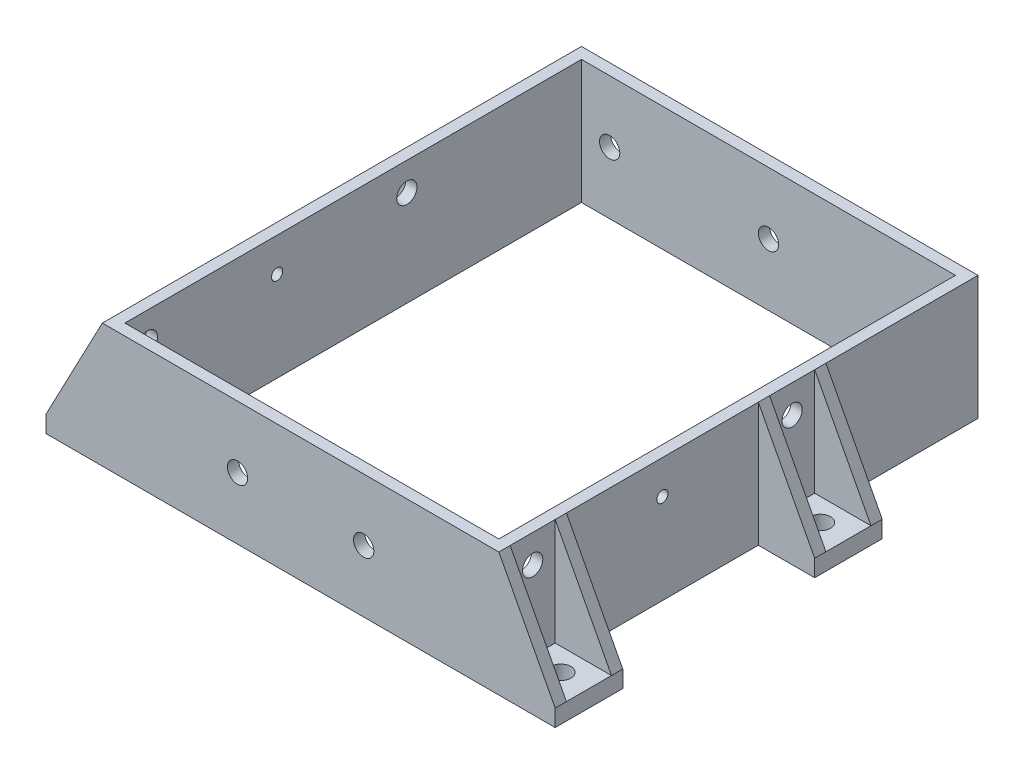
SolidWorks part; units mm, degrees
ref_plane "前视基准面" through (0, 0, 0) normal (0, 0, 1) x (1, 0, 0)
ref_plane "上视基准面" through (0, 0, 0) normal (0, 1, 0) x (1, 0, 0)
ref_plane "右视基准面" through (0, 0, 0) normal (1, 0, 0) x (0, 0, -1)
sketch "Sketch1" plane through (0, 0, 0) normal (0, 1, 0) x (1, 0, 0)
  line L1 (0, 0) -> (50, 0)
  line L2 (0, 0) -> (0, 9.1)
  line L3 (0, 9.1) -> (50, 9.1)
  line L4 (50, 0) -> (50, 9.1)
  dimension "D1" = 50
  dimension "D2" = 9.1
extrude "Boss-Extrude1" add sketch "Sketch1" along normal blind 2
sketch "Sketch2" plane through (0, 2, 0) normal (0, 1, 0) x (1, 0, 0)
  line L0 (50, 9.1) -> (0, 9.1) construction
  line L1 (12.5, 9.1) -> (37.5, 9.1)
  line L2 (12.5, 9.1) -> (12.5, 2.5)
  line L3 (12.5, 2.5) -> (37.5, 2.5)
  line L4 (37.5, 9.1) -> (37.5, 2.5)
  line L5 (0, 9.1) -> (0, 0) construction
  line L6 (50, 0) -> (50, 9.1) construction
  point P8 (50, 4.55)
  dimension "D1" = 6.6
  dimension "D2" = 12.5
  dimension "D3" = 12.5
extrude "Cut-Extrude1" cut sketch "Sketch2" against normal blind 2
sketch "Sketch3" plane through (0, 2, 0) normal (0, 1, 0) x (1, 0, 0)
  line L0 (12.5, 9.1) -> (0, 9.1) construction
  line L1 (50, 9.1) -> (37.5, 9.1) construction
  line L3 (37.5, 2.5) -> (37.5, 9.1) construction
  line L5 (0, 9.1) -> (0, 0) construction
  circle A0 centre (6.25, 5.8) radius 1.8
  circle A1 centre (43.75, 5.8) radius 1.8
  dimension "D1" = 3.6
  dimension "D2" = 3.6
  dimension "D4" = 3.3
  dimension "D3" = 3.3
  dimension "D5" = 6.25
  dimension "D6" = 6.25
extrude "Cut-Extrude2" cut sketch "Sketch3" against normal blind 2
sketch "Sketch4" plane through (0, 2, 0) normal (0, 1, 0) x (1, 0, 0)
  line L0 (0, 0) -> (50, 0) construction
  line L1 (-8.2, 0) -> (58.2, 0)
  line L2 (-8.2, 0) -> (-8.2, -130)
  line L3 (-8.2, -130) -> (58.2, -130)
  line L4 (58.2, 0) -> (58.2, -130)
  line L5 (12.5, 2.5) -> (37.5, 2.5) construction
  point P6 (25, 2.5)
  dimension "D1" = 130
  dimension "D2" = 0
  dimension "D3" = 33.2
  dimension "D4" = 66.4
extrude "Boss-Extrude2" add sketch "Sketch4" against normal blind 2
sketch "Sketch5" plane through (0, 0, 130) normal (0, 0, 1) x (1, 0, 0)
  line L1 (-8.2, 2) -> (58.2, 2)
  line L2 (-8.2, 2) -> (-8.2, 0)
  line L3 (-8.2, 0) -> (58.2, 0)
  line L4 (58.2, 2) -> (58.2, 0)
extrude "Boss-Extrude3" add sketch "Sketch5" along normal blind 2.5
sketch "Sketch6" plane through (0, 2, 0) normal (0, 1, 0) x (1, 0, 0)
  line L1 (-8.2, -132.5) -> (-16.8, -132.5)
  line L2 (-8.2, -132.5) -> (-8.2, -70)
  line L3 (-8.2, -70) -> (-16.8, -70)
  line L4 (-16.8, -132.5) -> (-16.8, -70)
  line L5 (58.2, -132.5) -> (66.8, -132.5)
  line L6 (58.2, -132.5) -> (58.2, -70)
  line L7 (58.2, -70) -> (66.8, -70)
  line L8 (66.8, -132.5) -> (66.8, -70)
  dimension "D1" = 8.6
  dimension "D2" = 8.6
  dimension "D3" = 62.5
  dimension "D4" = 62.5
extrude "Boss-Extrude4" add sketch "Sketch6" against normal blind 2
sketch "Sketch7" plane through (0, 2, 0) normal (0, 1, 0) x (1, 0, 0)
  line L0 (-13.5, -64.2883) -> (-13.5, -157.5169) construction
  line L1 (63.5, -64.2883) -> (63.5, -152.5529) construction
  line L2 (-16.8, -70) -> (-16.8, -132.5) construction
  line L3 (66.8, -132.5) -> (66.8, -70) construction
  line L4 (-8.2, -70) -> (-16.8, -70) construction
  line L5 (66.8, -132.5) -> (-16.8, -132.5) construction
  line L6 (66.8, -70) -> (58.2, -70) construction
  line L7 (-15, -115) -> (-12, -115)
  line L8 (-15, -115) -> (-15, -120)
  line L9 (-15, -120) -> (-12, -120)
  line L10 (-12, -115) -> (-12, -120)
  line L11 (62, -115) -> (65, -115)
  line L12 (62, -115) -> (62, -120)
  line L13 (62, -120) -> (65, -120)
  line L14 (65, -115) -> (65, -120)
  circle A0 centre (-13.5, -77) radius 1.8
  circle A1 centre (-13.5, -101.25) radius 1.8
  circle A2 centre (-13.5, -125.5) radius 1.8
  circle A3 centre (63.5, -77) radius 1.8
  circle A4 centre (63.5, -101.25) radius 1.8
  circle A5 centre (63.5, -125.5) radius 1.8
  dimension "D3" = 3.6
  dimension "D4" = 3.6
  dimension "D6" = 3.6
  dimension "D12" = 3.6
  dimension "D13" = 3.6
  dimension "D14" = 3.6
  dimension "D1" = 3.3
  dimension "D2" = 3.3
  dimension "D5" = 31.25
  dimension "D7" = 7
  dimension "D8" = 1.5
  dimension "D9" = 3
  dimension "D10" = 5
  dimension "D11" = 12.5
  dimension "D15" = 1.5
  dimension "D16" = 3
  dimension "D17" = 7
  dimension "D18" = 7
extrude "Cut-Extrude3" cut sketch "Sketch7" against normal blind 2
sketch "Sketch8" plane through (0, 2, 0) normal (0, 1, 0) x (1, 0, 0)
  line L0 (25, 2.5) -> (25, -143.8166) construction
  line L1 (12.5, 2.5) -> (37.5, 2.5) construction
  line L3 (12.5, 0) -> (37.5, 0)
  line L4 (12.5, 0) -> (12.5, -45)
  line L5 (12.5, -45) -> (37.5, -45)
  line L6 (37.5, 0) -> (37.5, -45)
  dimension "D1" = 25
  dimension "D2" = 12.5
  dimension "D3" = 45
extrude "Cut-Extrude4" cut sketch "Sketch8" against normal blind 20
sketch "Sketch9" plane through (0, 2, 0) normal (0, 1, 0) x (1, 0, 0)
  line L0 (37.5, -45) -> (37.5, 0) construction
  line L1 (12.5, 0) -> (37.5, 0)
  line L2 (12.5, 0) -> (12.5, -10)
  line L3 (12.5, -10) -> (37.5, -10)
  line L4 (37.5, 0) -> (37.5, -10)
  dimension "D1" = 10
extrude "Boss-Extrude5" add sketch "Sketch9" against normal blind 2
sketch "Sketch10" plane through (0, 2, 0) normal (0, 1, 0) x (1, 0, 0)
  line L0 (-8.2, 0) -> (-8.2, -70) construction
  line L1 (-8.2, -16) -> (-42.9, -16)
  line L2 (-8.2, -16) -> (-8.2, -43.07)
  line L3 (-8.2, -43.07) -> (-42.9, -43.07)
  line L4 (-42.9, -16) -> (-42.9, -43.07)
  line L5 (0, 0) -> (-8.2, 0) construction
  line L6 (58.2, -70) -> (58.2, 0) construction
  line L7 (58.2, -16) -> (92.9, -16)
  line L8 (58.2, -16) -> (58.2, -43.07)
  line L9 (58.2, -43.07) -> (92.9, -43.07)
  line L10 (92.9, -16) -> (92.9, -43.07)
  dimension "D1" = 16
  dimension "D2" = 27.07
  dimension "D3" = 34.7
  dimension "D4" = 34.7
extrude "Boss-Extrude6" add sketch "Sketch10" against normal blind 2
sketch "Sketch11" plane through (0, 2, 0) normal (0, 1, 0) x (1, 0, 0)
  line L0 (-48.2559, -39.82) -> (25.7485, -39.82) construction
  line L1 (-47.1851, -19.25) -> (20.7514, -19.25) construction
  line L2 (-8.2, -16) -> (-42.9, -16) construction
  line L3 (-42.9, -43.07) -> (-8.2, -43.07) construction
  line L4 (-42.9, -16) -> (-42.9, -43.07) construction
  circle A0 centre (-36.9, -19.25) radius 1.8
  circle A1 centre (-36.9, -39.82) radius 1.8
  circle A2 centre (-22.6, -19.25) radius 1.8
  circle A3 centre (-22.6, -39.82) radius 1.8
  dimension "D5" = 3.6
  dimension "D6" = 3.6
  dimension "D7" = 3.6
  dimension "D8" = 3.6
  dimension "D10" = 20.3
  dimension "D1" = 3.25
  dimension "D2" = 3.25
  dimension "D3" = 6
  dimension "D4" = 6
  dimension "D9" = 20.3
extrude "Cut-Extrude5" cut sketch "Sketch11" against normal blind 2
sketch "Sketch12" plane through (0, 2, 0) normal (0, 1, 0) x (1, 0, 0)
  line L0 (39.2942, -19.25) -> (115.8735, -19.25) construction
  line L1 (40.8036, -39.82) -> (109.9769, -39.82) construction
  line L2 (92.9, -43.07) -> (92.9, -16) construction
  circle A0 centre (72.6, -19.25) radius 1.8
  circle A1 centre (86.9, -19.25) radius 1.8
  circle A2 centre (72.6, -39.82) radius 1.8
  circle A3 centre (86.9, -39.82) radius 1.8
  dimension "D1" = 3.6
  dimension "D2" = 3.6
  dimension "D5" = 3.6
  dimension "D6" = 3.6
  dimension "D3" = 6
  dimension "D4" = 20.3
extrude "Cut-Extrude6" cut sketch "Sketch12" against normal blind 2
sketch "Sketch13" plane through (-42.9, 0, 0) normal (-1, 0, 0) x (0, 0, 1)
  line L1 (16, 2) -> (14, 2)
  line L2 (16, 2) -> (16, 0)
  line L3 (16, 0) -> (14, 0)
  line L4 (14, 2) -> (14, 0)
  line L5 (43.07, 2) -> (45.07, 2)
  line L6 (43.07, 2) -> (43.07, 0)
  line L7 (43.07, 0) -> (45.07, 0)
  line L8 (45.07, 2) -> (45.07, 0)
  dimension "D1" = 2
  dimension "D2" = 2
extrude "Boss-Extrude7" add sketch "Sketch13" against normal blind 44
sketch "Sketch14" plane through (92.9, 0, 0) normal (1, 0, 0) x (0, 0, -1)
  line L1 (-16, 2) -> (-14, 2)
  line L2 (-16, 2) -> (-16, 0)
  line L3 (-16, 0) -> (-14, 0)
  line L4 (-14, 2) -> (-14, 0)
  line L5 (-43.07, 0) -> (-45.07, 0)
  line L6 (-43.07, 0) -> (-43.07, 2)
  line L7 (-43.07, 2) -> (-45.07, 2)
  line L8 (-45.07, 0) -> (-45.07, 2)
  dimension "D1" = 2
  dimension "D2" = 2
extrude "Boss-Extrude8" add sketch "Sketch14" against normal blind 46
sketch "Sketch16" plane through (0, 2, 0) normal (0, 1, 0) x (1, 0, 0)
  line L0 (66.8, -132.5) -> (-16.8, -132.5) construction
  line L1 (4, -132.5) -> (46, -132.5)
  line L2 (4, -132.5) -> (4, -175.5)
  line L3 (4, -175.5) -> (46, -175.5)
  line L4 (46, -132.5) -> (46, -175.5)
  line L5 (37.5, -45) -> (12.5, -45) construction
  point P6 (25, -45)
  dimension "D1" = 42
  dimension "D2" = 43
  dimension "D3" = 21
extrude "Boss-Extrude10" add sketch "Sketch16" against normal blind 2
sketch "Sketch18" plane through (0, 2, 0) normal (0, 1, 0) x (1, 0, 0)
  line L0 (4, -175.5) -> (46, -175.5) construction
  line L1 (4, -132.5) -> (4, -175.5) construction
  line L2 (46, -175.5) -> (46, -132.5) construction
  line L3 (4, -132.5) -> (-16.8, -132.5) construction
  line L4 (66.8, -132.5) -> (46, -132.5) construction
  circle A0 centre (8.74, -171.03) radius 1.8
  circle A1 centre (41.26, -171.03) radius 1.8
  circle A2 centre (8.74, -138.5) radius 1.8
  circle A3 centre (41.26, -138.5) radius 1.8
  dimension "D3" = 3.6
  dimension "D6" = 3.6
  dimension "D7" = 3.6
  dimension "D8" = 3.6
  dimension "D1" = 4.47
  dimension "D2" = 4.74
  dimension "D4" = 4.47
  dimension "D5" = 4.74
  dimension "D9" = 6
  dimension "D10" = 6
extrude "Cut-Extrude7" cut sketch "Sketch18" against normal blind 2
sketch "Sketch20" plane through (0, 2, 0) normal (0, 1, 0) x (1, 0, 0)
  line L0 (-2, -132.5) -> (4, -132.5)
  line L1 (4, -132.5) -> (-16.8, -132.5) construction
  line L2 (4, -132.5) -> (4, -138.5)
  line L3 (4, -132.5) -> (4, -175.5) construction
  line L4 (46, -138.5) -> (46, -132.5)
  line L5 (46, -175.5) -> (46, -132.5) construction
  line L6 (46, -132.5) -> (52, -132.5)
  line L7 (66.8, -132.5) -> (46, -132.5) construction
  arc A0 (-2, -132.5) -> (4, -138.5) centre (-2, -138.5) cw
  arc A1 (52, -132.5) -> (46, -138.5) centre (52, -138.5) ccw
  dimension "D1" = 6
  dimension "D2" = 6
  dimension "D3" = 6
extrude "Boss-Extrude12" add sketch "Sketch20" against normal blind 2 contours L0 A0 L2 | A1 L6 L4
sketch "Sketch21" plane through (0, 0, -9.1) normal (0, 0, -1) x (-1, 0, 0)
  line L1 (-50, 2) -> (-52, 2)
  line L2 (-50, 2) -> (-50, 0)
  line L3 (-50, 0) -> (-52, 0)
  line L4 (-52, 2) -> (-52, 0)
  line L5 (-37.5, 2) -> (-35.5, 2)
  line L6 (-37.5, 2) -> (-37.5, 0)
  line L7 (-37.5, 0) -> (-35.5, 0)
  line L8 (-35.5, 2) -> (-35.5, 0)
  line L9 (-12.5, 2) -> (-14.5, 2)
  line L10 (-12.5, 2) -> (-12.5, 0)
  line L11 (-12.5, 0) -> (-14.5, 0)
  line L12 (-14.5, 2) -> (-14.5, 0)
  line L13 (0, 2) -> (2, 2)
  line L14 (0, 2) -> (0, 0)
  line L15 (0, 0) -> (2, 0)
  line L16 (2, 2) -> (2, 0)
  dimension "D1" = 2
  dimension "D2" = 2
  dimension "D3" = 2
  dimension "D4" = 2
extrude "Boss-Extrude13" add sketch "Sketch21" against normal blind 10
sketch "Sketch25" plane through (0, 2, 0) normal (0, 1, 0) x (1, 0, 0)
  line L0 (-11.7, -6.4239) -> (-11.7, -56.5762) construction
  line L1 (-8.2, 0) -> (-8.2, -14) construction
  line L2 (61.7, -6.4239) -> (61.7, -56.5762) construction
  line L3 (58.2, -14) -> (58.2, 0) construction
  line L4 (-8.2, -14) -> (-42.9, -14) construction
  line L5 (-13.2, -20) -> (-10.2, -20)
  line L6 (-13.2, -20) -> (-13.2, -25)
  line L7 (-13.2, -25) -> (-10.2, -25)
  line L8 (-10.2, -20) -> (-10.2, -25)
  line L9 (-8.2, -45.07) -> (-42.9, -45.07) construction
  line L10 (-13.2, -34.07) -> (-10.2, -34.07)
  line L11 (-13.2, -34.07) -> (-13.2, -39.07)
  line L12 (-13.2, -39.07) -> (-10.2, -39.07)
  line L13 (-10.2, -34.07) -> (-10.2, -39.07)
  line L14 (58.2, -14) -> (92.9, -14) construction
  line L15 (60.2, -20) -> (63.2, -20)
  line L16 (60.2, -20) -> (60.2, -25)
  line L17 (60.2, -25) -> (63.2, -25)
  line L18 (63.2, -20) -> (63.2, -25)
  line L19 (60.2, -34.07) -> (63.2, -34.07)
  line L20 (60.2, -34.07) -> (60.2, -39.07)
  line L21 (60.2, -39.07) -> (63.2, -39.07)
  line L22 (63.2, -34.07) -> (63.2, -39.07)
  line L23 (58.2, -45.07) -> (92.9, -45.07) construction
  dimension "D1" = 3.5
  dimension "D2" = 3.5
  dimension "D3" = 3
  dimension "D4" = 1.5
  dimension "D5" = 5
  dimension "D6" = 6
  dimension "D7" = 5
  dimension "D8" = 6
  dimension "D9" = 3
  dimension "D10" = 1.5
  dimension "D11" = 1.5
  dimension "D12" = 3
  dimension "D13" = 1.5
  dimension "D14" = 3
  dimension "D15" = 6
  dimension "D16" = 6
extrude "Cut-Extrude8" cut sketch "Sketch25" against normal blind 10
sketch "Sketch26" plane through (0, 2, 0) normal (0, 1, 0) x (1, 0, 0)
  line L1 (-2, 0) -> (-8.2, 0)
  line L2 (-2, 0) -> (-2, 13)
  line L3 (-2, 13) -> (-8.2, 13)
  line L4 (-8.2, 0) -> (-8.2, 13)
  line L5 (58.2, 0) -> (52, 0)
  line L6 (58.2, 0) -> (58.2, 13)
  line L7 (58.2, 13) -> (52, 13)
  line L8 (52, 0) -> (52, 13)
  line L9 (-2, 13) -> (52, 13)
  line L10 (-2, 13) -> (-2, 9.1)
  line L11 (-2, 9.1) -> (52, 9.1)
  line L12 (52, 13) -> (52, 9.1)
  line L13 (35.5, 2.5) -> (14.5, 2.5)
  line L14 (35.5, 2.5) -> (35.5, 9.1)
  line L15 (35.5, 9.1) -> (14.5, 9.1)
  line L16 (14.5, 2.5) -> (14.5, 9.1)
  dimension "D1" = 13
extrude "Boss-Extrude14" add sketch "Sketch26" against normal blind 2 contours L4 L1 L2 L3 | L2 L11 L8 L9 | L16 L13 L14 L11 | L8 L5 L6 L7
sketch "Sketch27" plane through (0, 2, 0) normal (0, 1, 0) x (1, 0, 0)
  line L0 (-8.2, -14) -> (-42.9, -14) construction
  line L1 (-8.2, 13) -> (-10.2, 13)
  line L2 (-8.2, 13) -> (-8.2, -14)
  line L3 (-8.2, -14) -> (-10.2, -14)
  line L4 (-10.2, 13) -> (-10.2, -14)
  line L5 (-8.2, -45.07) -> (-42.9, -45.07) construction
  line L6 (-10.2, -45.07) -> (-8.2, -45.07)
  line L7 (-10.2, -45.07) -> (-10.2, -70)
  line L8 (-10.2, -70) -> (-8.2, -70)
  line L9 (-8.2, -45.07) -> (-8.2, -70)
  line L10 (58.2, -14) -> (92.9, -14) construction
  line L11 (58.2, 13) -> (60.2, 13)
  line L12 (58.2, 13) -> (58.2, -14)
  line L13 (58.2, -14) -> (60.2, -14)
  line L14 (60.2, 13) -> (60.2, -14)
  line L15 (66.8, -70) -> (58.2, -70) construction
  line L16 (58.2, -45.07) -> (60.2, -45.07)
  line L17 (58.2, -45.07) -> (58.2, -70)
  line L18 (58.2, -70) -> (60.2, -70)
  line L19 (60.2, -45.07) -> (60.2, -70)
extrude "Boss-Extrude15" add sketch "Sketch27" against normal blind 2
sketch "Sketch29" plane through (0, 2, 0) normal (0, 1, 0) x (1, 0, 0)
  line L1 (-10.2, -14) -> (-20.2, -14)
  line L2 (-10.2, -14) -> (-10.2, -4)
  line L3 (-10.2, -4) -> (-20.2, -4)
  line L4 (-20.2, -14) -> (-20.2, -4)
  line L5 (-10.2, -45.07) -> (-20.2, -45.07)
  line L6 (-10.2, -45.07) -> (-10.2, -55.07)
  line L7 (-10.2, -55.07) -> (-20.2, -55.07)
  line L8 (-20.2, -45.07) -> (-20.2, -55.07)
  line L9 (60.2, -14) -> (70.2, -14)
  line L10 (60.2, -14) -> (60.2, -4)
  line L11 (60.2, -4) -> (70.2, -4)
  line L12 (70.2, -14) -> (70.2, -4)
  line L13 (60.2, -45.07) -> (70.2, -45.07)
  line L14 (60.2, -45.07) -> (60.2, -55.07)
  line L15 (60.2, -55.07) -> (70.2, -55.07)
  line L16 (70.2, -45.07) -> (70.2, -55.07)
  dimension "D1" = 10
  dimension "D2" = 10
  dimension "D3" = 10
  dimension "D4" = 10
  dimension "D5" = 10
  dimension "D6" = 10
  dimension "D7" = 10
extrude "Boss-Extrude19" add sketch "Sketch29" against normal blind 2
sketch "Sketch41" plane through (0, 2, 0) normal (0, 1, 0) x (1, 0, 0)
  circle A0 centre (-15.2, -9) radius 1.8
  circle A1 centre (-15.2, -50.07) radius 1.8
  circle A2 centre (65.2, -9) radius 1.8
  circle A3 centre (65.2, -50.07) radius 1.8
  dimension "D1" = 3.6
  dimension "D2" = 3.6
  dimension "D3" = 3.6
  dimension "D4" = 3.6
extrude "Cut-Extrude15" cut sketch "Sketch41" against normal blind 2
sketch "Sketch42" plane through (0, 2, 0) normal (0, 1, 0) x (1, 0, 0)
  line L0 (60.2, -70) -> (60.2, -55.07) construction
  line L1 (-10.2, -70) -> (-16.8, -70) construction
  line L2 (-16.8, -70) -> (-10.2, -70)
  line L3 (-10.2, -70) -> (-10.2, -63.4)
  line L4 (60.2, -63.4) -> (60.2, -70)
  line L5 (60.2, -70) -> (66.8, -70)
  arc A0 (-16.8, -70) -> (-10.2, -63.4) centre (-16.8, -63.4) ccw
  arc A1 (66.8, -70) -> (60.2, -63.4) centre (66.8, -63.4) cw
  dimension "D1" = 6.6
extrude "Boss-Extrude26" add sketch "Sketch42" against normal blind 2
sketch "Sketch43" plane through (0, 0, -13) normal (0, 0, -1) x (-1, 0, 0)
  line L1 (10.2, 2) -> (-60.2, 2)
  line L2 (10.2, 2) -> (10.2, 0)
  line L3 (10.2, 0) -> (-60.2, 0)
  line L4 (-60.2, 2) -> (-60.2, 0)
extrude "Boss-Extrude27" add sketch "Sketch43" along normal blind 11
sketch "Sketch44" plane through (0, 2, 0) normal (0, 1, 0) x (1, 0, 0)
  line L0 (-10.2, -55.07) -> (-10.2, -63.4) construction
  line L1 (-20.2, -55.07) -> (-10.2, -55.07)
  line L2 (-20.2, -55.07) -> (-20.2, -60.07)
  line L3 (-20.2, -60.07) -> (-10.2, -60.07)
  line L4 (-10.2, -55.07) -> (-10.2, -60.07)
  line L5 (60.2, -63.4) -> (60.2, -55.07) construction
  line L6 (70.2, -55.07) -> (60.2, -55.07)
  line L7 (70.2, -55.07) -> (70.2, -60.07)
  line L8 (70.2, -60.07) -> (60.2, -60.07)
  line L9 (60.2, -55.07) -> (60.2, -60.07)
  dimension "D1" = 5
extrude "Boss-Extrude28" add sketch "Sketch44" against normal blind 2
sketch "Sketch45" plane through (0, 2, 0) normal (0, 1, 0) x (1, 0, 0)
  circle A0 centre (-15.2, -50.07) radius 1.8
  circle A1 centre (65.2, -50.07) radius 1.8
extrude "Boss-Extrude29" add sketch "Sketch45" against normal blind 2
sketch "Sketch46" plane through (0, 2, 0) normal (0, 1, 0) x (1, 0, 0)
  line L0 (-20.2, -60.07) -> (-10.2, -60.07) construction
  line L1 (60.2, -60.07) -> (70.2, -60.07) construction
  line L2 (-20.2, -45.07) -> (-20.2, -60.07) construction
  line L3 (70.2, -60.07) -> (70.2, -45.07) construction
  circle A0 centre (-15.2, -55.07) radius 1.8
  circle A1 centre (65.2, -55.07) radius 1.8
  dimension "D2" = 3.6
  dimension "D3" = 3.6
  dimension "D1" = 5
  dimension "D4" = 5
  dimension "D5" = 5
  dimension "D6" = 5
extrude "Cut-Extrude16" cut sketch "Sketch46" against normal blind 2
sketch "Sketch47" plane through (0, 2, 0) normal (0, 1, 0) x (1, 0, 0)
  line L0 (-10.2, 24) -> (-10.2, -4) construction
  line L1 (-20.2, -4) -> (-10.2, -4)
  line L2 (-20.2, -4) -> (-20.2, -3)
  line L3 (-20.2, -3) -> (-10.2, -3)
  line L4 (-10.2, -4) -> (-10.2, -3)
  line L5 (-10.2, -60.07) -> (-10.2, -63.4) construction
  line L6 (-20.2, -60.07) -> (-10.2, -60.07)
  line L7 (-20.2, -60.07) -> (-20.2, -61.07)
  line L8 (-20.2, -61.07) -> (-10.2, -61.07)
  line L9 (-10.2, -60.07) -> (-10.2, -61.07)
  line L10 (60.2, -63.4) -> (60.2, -60.07) construction
  line L11 (60.2, -4) -> (70.2, -4)
  line L12 (60.2, -4) -> (60.2, -3)
  line L13 (60.2, -3) -> (70.2, -3)
  line L14 (70.2, -4) -> (70.2, -3)
  line L15 (70.2, -60.07) -> (60.2, -60.07)
  line L16 (70.2, -60.07) -> (70.2, -61.07)
  line L17 (70.2, -61.07) -> (60.2, -61.07)
  line L18 (60.2, -60.07) -> (60.2, -61.07)
  dimension "D1" = 1
  dimension "D2" = 1
extrude "Boss-Extrude30" add sketch "Sketch47" against normal blind 2
sketch "Sketch48" plane through (0, 2, 0) normal (0, 1, 0) x (1, 0, 0)
  line L1 (-42.9, -14) -> (-10.2, -14)
  line L2 (-42.9, -14) -> (-42.9, -45.07)
  line L3 (-42.9, -45.07) -> (-10.2, -45.07)
  line L4 (-10.2, -14) -> (-10.2, -45.07)
  line L5 (92.9, -14) -> (60.2, -14)
  line L6 (92.9, -14) -> (92.9, -45.07)
  line L7 (92.9, -45.07) -> (60.2, -45.07)
  line L8 (60.2, -14) -> (60.2, -45.07)
  line L9 (-20.2, -61.07) -> (81.55, -61.07)
  line L10 (-20.2, -61.07) -> (-20.2, -181.5574)
  line L11 (-20.2, -181.5574) -> (81.55, -181.5574)
  line L12 (81.55, -61.07) -> (81.55, -181.5574)
extrude "Cut-Extrude17" cut sketch "Sketch48" against normal blind 20
sketch "Sketch50" plane through (0, 2, 0) normal (0, 1, 0) x (1, 0, 0)
  line L0 (-10.2, 24) -> (-10.2, -3) construction
  line L1 (-8.2, 22) -> (58.2, 22)
  line L2 (-8.2, 22) -> (-8.2, -59.07)
  line L3 (-8.2, -59.07) -> (58.2, -59.07)
  line L4 (58.2, 22) -> (58.2, -59.07)
  line L5 (-10.2, 24) -> (60.2, 24) construction
  line L6 (-20.2, -61.07) -> (70.2, -61.07) construction
  line L7 (60.2, -3) -> (60.2, 24) construction
  dimension "D1" = 2
  dimension "D2" = 2
  dimension "D3" = 2
  dimension "D4" = 2
extrude "Cut-Extrude19" cut sketch "Sketch50" against normal blind 20
sketch "Sketch51" plane through (0, 2, 0) normal (0, 1, 0) x (1, 0, 0)
  line L0 (-20.2, -61.07) -> (70.2, -61.07) construction
  line L1 (-10.2, 24) -> (60.2, 24)
  line L2 (-10.2, 24) -> (-10.2, -61.07)
  line L3 (-10.2, -61.07) -> (60.2, -61.07)
  line L4 (60.2, 24) -> (60.2, -61.07)
  line L6 (58.2, -59.07) -> (-8.2, -59.07)
  line L7 (58.2, -59.07) -> (58.2, 22)
  line L8 (58.2, 22) -> (-8.2, 22)
  line L9 (-8.2, -59.07) -> (-8.2, 22)
extrude "Boss-Extrude31" add sketch "Sketch51" along normal blind 20
sketch "Sketch52" plane through (0, 2, 0) normal (0, 1, 0) x (1, 0, 0)
  line L0 (-10.2, 24) -> (-10.2, -61.07) construction
  line L1 (-20.2, -14) -> (-10.2, -14)
  line L2 (-20.2, -14) -> (-20.2, -15)
  line L3 (-20.2, -15) -> (-10.2, -15)
  line L4 (-10.2, -14) -> (-10.2, -15)
  line L5 (60.2, -61.07) -> (60.2, 24) construction
  line L6 (70.2, -14) -> (60.2, -14)
  line L7 (70.2, -14) -> (70.2, -15)
  line L8 (70.2, -15) -> (60.2, -15)
  line L9 (60.2, -14) -> (60.2, -15)
  dimension "D1" = 1
extrude "Boss-Extrude32" add sketch "Sketch52" against normal blind 2
sketch "Sketch53" plane through (0, 2, 0) normal (0, 1, 0) x (1, 0, 0)
  line L0 (-10.2, 24) -> (-10.2, -61.07) construction
  line L1 (-20.2, -45.07) -> (-10.2, -45.07)
  line L2 (-20.2, -45.07) -> (-20.2, -49.07)
  line L3 (-20.2, -49.07) -> (-10.2, -49.07)
  line L4 (-10.2, -45.07) -> (-10.2, -49.07)
  line L5 (60.2, -61.07) -> (60.2, 24) construction
  line L6 (70.2, -45.07) -> (60.2, -45.07)
  line L7 (70.2, -45.07) -> (70.2, -49.07)
  line L8 (70.2, -49.07) -> (60.2, -49.07)
  line L9 (60.2, -45.07) -> (60.2, -49.07)
  dimension "D1" = 4
  dimension "D2" = 4
extrude "Cut-Extrude20" cut sketch "Sketch53" against normal blind 2
sketch "Sketch54" plane through (0, 2, 0) normal (0, 1, 0) x (1, 0, 0)
  line L1 (-20.2, -3) -> (-10.2, -3)
  line L2 (-20.2, -3) -> (-20.2, -15)
  line L3 (-20.2, -15) -> (-10.2, -15)
  line L4 (-10.2, -3) -> (-10.2, -15)
  line L5 (-20.2, -49.07) -> (-10.2, -49.07)
  line L6 (-20.2, -49.07) -> (-20.2, -61.07)
  line L7 (-20.2, -61.07) -> (-10.2, -61.07)
  line L8 (-10.2, -49.07) -> (-10.2, -61.07)
  line L9 (60.2, -3) -> (70.2, -3)
  line L10 (60.2, -3) -> (60.2, -15)
  line L11 (60.2, -15) -> (70.2, -15)
  line L12 (70.2, -3) -> (70.2, -15)
  line L13 (60.2, -49.07) -> (70.2, -49.07)
  line L14 (60.2, -49.07) -> (60.2, -61.07)
  line L15 (60.2, -61.07) -> (70.2, -61.07)
  line L16 (70.2, -49.07) -> (70.2, -61.07)
  circle A0 centre (-15.2, -9) radius 1.8
  circle A1 centre (-15.2, -55.07) radius 1.8
  circle A2 centre (65.2, -9) radius 1.8
  circle A3 centre (65.2, -55.07) radius 1.8
extrude "Boss-Extrude33" add sketch "Sketch54" along normal blind 1
sketch "Sketch55" plane through (0, 0, 3) normal (0, 0, -1) x (-1, 0, 0)
  line L0 (20.2, 3) -> (10.2, 22)
  line L1 (10.2, 22) -> (10.2, 3)
  line L2 (10.2, 3) -> (20.2, 3)
  line L3 (-70.2, 3) -> (-60.2, 3)
  line L4 (-60.2, 3) -> (-60.2, 22)
  line L5 (-60.2, 22) -> (-70.2, 3)
sketch "Sketch56" plane through (0, 0, 15) normal (0, 0, 1) x (1, 0, 0)
  line L0 (-20.2, 3) -> (-10.2, 3)
  line L1 (-10.2, 3) -> (-10.2, 22)
  line L2 (-10.2, 22) -> (-20.2, 3)
  line L3 (70.2, 3) -> (60.2, 3)
  line L4 (60.2, 3) -> (60.2, 22)
  line L5 (60.2, 22) -> (70.2, 3)
sketch "Sketch57" plane through (0, 0, 49.07) normal (0, 0, -1) x (-1, 0, 0)
  line L0 (20.2, 3) -> (10.2, 3)
  line L1 (10.2, 22) -> (20.2, 3)
  line L2 (-70.2, 3) -> (-60.2, 3)
  line L3 (-60.2, 3) -> (-60.2, 22)
  line L4 (-60.2, 22) -> (-70.2, 3)
  line L5 (10.2, 3) -> (10.2, 22)
sketch "Sketch59" plane through (0, 0, -22) normal (0, 0, 1) x (1, 0, 0)
  line L0 (-8.2, 11) -> (58.2, 11) construction
  line L1 (-8.2, 0) -> (-8.2, 22) construction
  line L2 (58.2, 0) -> (58.2, 22) construction
  circle A0 centre (-3.2, 11) radius 1.8
  circle A1 centre (53.2, 11) radius 1.8
  circle A2 centre (25, 11) radius 1.8
  dimension "D1" = 3.6
  dimension "D2" = 3.6
  dimension "D5" = 3.6
  dimension "D3" = 5
  dimension "D4" = 5
extrude "Cut-Extrude23" cut sketch "Sketch59" against normal blind 16 and the other way blind 96
sketch "Sketch62" plane through (0, 0, 61.07) normal (0, 0, 1) x (1, 0, 0)
  line L1 (-8.5777, 16.369) -> (58.4073, 16.369)
  line L2 (-8.5777, 16.369) -> (-8.5777, 5.1196)
  line L3 (-8.5777, 5.1196) -> (58.4073, 5.1196)
  line L4 (58.4073, 16.369) -> (58.4073, 5.1196)
extrude "Boss-Extrude38" add sketch "Sketch62" against normal blind 1
sketch "Sketch65" plane through (0, 0, 59.07) normal (0, 0, -1) x (-1, 0, 0)
  line L0 (8.2, 11) -> (-58.2, 11) construction
  line L1 (8.2, 0) -> (8.2, 22) construction
  line L2 (-58.2, 0) -> (-58.2, 22) construction
  circle A0 centre (-13.8, 11) radius 1.8
  circle A1 centre (-36.2, 11) radius 1.8
  dimension "D2" = 3.6
  dimension "D4" = 3.6
  dimension "D1" = 22
  dimension "D3" = 22
extrude "Cut-Extrude27" cut sketch "Sketch65" against normal blind 3
sketch "Sketch66" plane through (-10.2, 0, 0) normal (-1, 0, 0) x (0, 0, 1)
  line L0 (-24, 22) -> (61.07, 22) construction
  circle A0 centre (32.035, 16) radius 1
  dimension "D1" = 6
  dimension "D2" = 2
extrude "Cut-Extrude28" cut sketch "Sketch66" against normal blind 87
extrude "Boss-Extrude41" add sketch "Sketch55" against normal blind 2
extrude "Boss-Extrude42" add sketch "Sketch56" against normal blind 2
extrude "Boss-Extrude43" add sketch "Sketch57" against normal blind 2
sketch "Sketch68" plane through (0, 0, 59.07) normal (0, 0, -1) x (-1, 0, 0)
  line L1 (-0.8965, 6.2744) -> (5.8953, 6.2744)
  line L2 (-0.8965, 6.2744) -> (-0.8965, 14.4185)
  line L3 (-0.8965, 14.4185) -> (5.8953, 14.4185)
  line L4 (5.8953, 6.2744) -> (5.8953, 14.4185)
  line L5 (-21.8815, 6.2744) -> (-27.3672, 6.2744)
  line L6 (-21.8815, 6.2744) -> (-21.8815, 14.4185)
  line L7 (-21.8815, 14.4185) -> (-27.3672, 14.4185)
  line L8 (-27.3672, 6.2744) -> (-27.3672, 14.4185)
  line L9 (-48.3497, 6.2744) -> (-56.1137, 6.2744)
  line L10 (-48.3497, 6.2744) -> (-48.3497, 17.9033)
  line L11 (-48.3497, 17.9033) -> (-56.1137, 17.9033)
  line L12 (-56.1137, 6.2744) -> (-56.1137, 17.9033)
extrude "Boss-Extrude44" add sketch "Sketch68" against normal blind 2
sketch "Sketch69" plane through (0, 0, 61.07) normal (0, 0, 1) x (1, 0, 0)
  line L0 (-20.2, 3) -> (-10.2, 3)
  line L1 (-10.2, 3) -> (-10.2, 22)
  line L2 (-10.2, 22) -> (-20.2, 3)
  line L3 (60.2, 3) -> (70.2, 3)
  line L4 (70.2, 3) -> (60.2, 22)
  line L5 (60.2, 22) -> (60.2, 3)
extrude "Boss-Extrude45" add sketch "Sketch69" against normal blind 2
sketch "Sketch70" plane through (-10.2, 0, 0) normal (-1, 0, 0) x (0, 0, 1)
  line L0 (5, 22) -> (13, 22) construction
  circle A0 centre (9, 17) radius 1.8
  circle A1 centre (55.07, 17) radius 1.8
  dimension "D1" = 3.6
  dimension "D3" = 3.6
  dimension "D2" = 5
extrude "Cut-Extrude29" cut sketch "Sketch70" against normal blind 83
